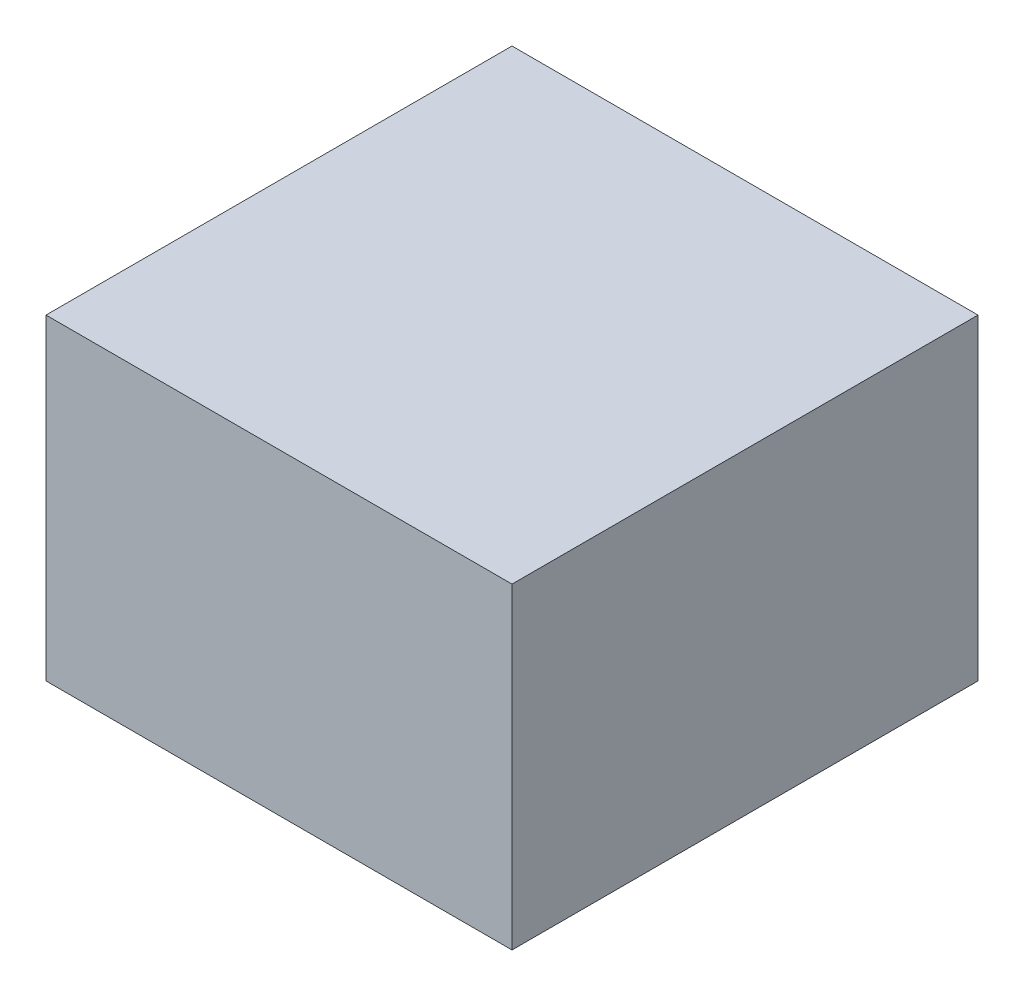
SolidWorks part; units mm, degrees
material "1060 Alloy"
ref_plane "Front Plane" through (0, 0, 0) normal (0, 0, 1) x (1, 0, 0)
ref_plane "Top Plane" through (0, 0, 0) normal (0, 1, 0) x (1, 0, 0)
ref_plane "Right Plane" through (0, 0, 0) normal (1, 0, 0) x (0, 0, -1)
sketch "Sketch1" plane through (0, 0, 0) normal (0, 1, 0) x (1, 0, 0)
  line L0 (0, 0) -> (50, 0)
  line L1 (50, 0) -> (50, 100)
  line L2 (50, 100) -> (-50, 100)
  line L3 (-50, 100) -> (-50, 0)
  line L4 (-50, 0) -> (0, 0)
  line L5 (50, 0) -> (100, 0)
  line L6 (100, 0) -> (150, 0)
  line L7 (150, 0) -> (150, 100)
  line L8 (150, 100) -> (50, 100)
  line L9 (50, 100) -> (50, 0)
  line L10 (150, 0) -> (200, 0)
  line L11 (200, 0) -> (250, 0)
  line L12 (250, 0) -> (250, 100)
  line L13 (250, 100) -> (150, 100)
  line L14 (150, 100) -> (150, 0)
  line L15 (250, 0) -> (300, 0)
  line L16 (300, 0) -> (350, 0)
  line L17 (350, 0) -> (350, 100)
  line L18 (350, 100) -> (250, 100)
  line L19 (250, 100) -> (250, 0)
  line L20 (350, 0) -> (400, 0)
  line L21 (400, 0) -> (450, 0)
  line L22 (450, 0) -> (450, 100)
  line L23 (450, 100) -> (350, 100)
  line L24 (350, 100) -> (350, 0)
  line L25 (50, 100) -> (100, 100)
  line L26 (100, 100) -> (150, 100)
  line L27 (150, 100) -> (150, 200)
  line L28 (150, 200) -> (50, 200)
  line L29 (50, 200) -> (50, 100)
  line L30 (150, 100) -> (200, 100)
  line L31 (200, 100) -> (250, 100)
  line L32 (250, 100) -> (250, 200)
  line L33 (250, 200) -> (150, 200)
  line L34 (150, 200) -> (150, 100)
  line L35 (250, 100) -> (300, 100)
  line L36 (300, 100) -> (350, 100)
  line L37 (350, 100) -> (350, 200)
  line L38 (350, 200) -> (250, 200)
  line L39 (250, 200) -> (250, 100)
  line L40 (350, 100) -> (400, 100)
  line L41 (400, 100) -> (450, 100)
  line L42 (450, 100) -> (450, 200)
  line L43 (450, 200) -> (350, 200)
  line L44 (350, 200) -> (350, 100)
  line L45 (50, 200) -> (100, 200)
  line L46 (100, 200) -> (150, 200)
  line L47 (150, 200) -> (150, 300)
  line L48 (150, 300) -> (50, 300)
  line L49 (50, 300) -> (50, 200)
  line L50 (150, 200) -> (200, 200)
  line L51 (200, 200) -> (250, 200)
  line L52 (250, 200) -> (250, 300)
  line L53 (250, 300) -> (150, 300)
  line L54 (150, 300) -> (150, 200)
  line L55 (250, 200) -> (300, 200)
  line L56 (300, 200) -> (350, 200)
  line L57 (350, 200) -> (350, 300)
  line L58 (350, 300) -> (250, 300)
  line L59 (250, 300) -> (250, 200)
  line L60 (350, 200) -> (400, 200)
  line L61 (400, 200) -> (450, 200)
  line L62 (450, 200) -> (450, 300)
  line L63 (450, 300) -> (350, 300)
  line L64 (350, 300) -> (350, 200)
  line L65 (50, 300) -> (100, 300)
  line L66 (100, 300) -> (150, 300)
  line L67 (150, 300) -> (150, 400)
  line L68 (150, 400) -> (50, 400)
  line L69 (50, 400) -> (50, 300)
  line L70 (150, 300) -> (200, 300)
  line L71 (200, 300) -> (250, 300)
  line L72 (250, 300) -> (250, 400)
  line L73 (250, 400) -> (150, 400)
  line L74 (150, 400) -> (150, 300)
  line L75 (250, 300) -> (300, 300)
  line L76 (300, 300) -> (350, 300)
  line L77 (350, 300) -> (350, 400)
  line L78 (350, 400) -> (250, 400)
  line L79 (250, 400) -> (250, 300)
  line L80 (350, 300) -> (400, 300)
  line L81 (400, 300) -> (450, 300)
  line L82 (450, 300) -> (450, 400)
  line L83 (450, 400) -> (350, 400)
  line L84 (350, 400) -> (350, 300)
  line L85 (50, 400) -> (100, 400)
  line L86 (100, 400) -> (150, 400)
  line L87 (150, 400) -> (150, 500)
  line L88 (150, 500) -> (50, 500)
  line L89 (50, 500) -> (50, 400)
  line L90 (150, 400) -> (200, 400)
  line L91 (200, 400) -> (250, 400)
  line L92 (250, 400) -> (250, 500)
  line L93 (250, 500) -> (150, 500)
  line L94 (150, 500) -> (150, 400)
  line L95 (250, 400) -> (300, 400)
  line L96 (300, 400) -> (350, 400)
  line L97 (350, 400) -> (350, 500)
  line L98 (350, 500) -> (250, 500)
  line L99 (250, 500) -> (250, 400)
  line L100 (350, 400) -> (400, 400)
  line L101 (400, 400) -> (450, 400)
  line L102 (450, 400) -> (450, 500)
  line L103 (450, 500) -> (350, 500)
  line L104 (350, 500) -> (350, 400)
  line L105 (-50, 100) -> (0, 100)
  line L106 (0, 100) -> (50, 100)
  line L107 (50, 100) -> (50, 200)
  line L108 (50, 200) -> (-50, 200)
  line L109 (-50, 200) -> (-50, 100)
  line L110 (-50, 200) -> (0, 200)
  line L111 (0, 200) -> (50, 200)
  line L112 (50, 200) -> (50, 300)
  line L113 (50, 300) -> (-50, 300)
  line L114 (-50, 300) -> (-50, 200)
  line L115 (-50, 300) -> (0, 300)
  line L116 (0, 300) -> (50, 300)
  line L117 (50, 300) -> (50, 400)
  line L118 (50, 400) -> (-50, 400)
  line L119 (-50, 400) -> (-50, 300)
  line L120 (-50, 400) -> (0, 400)
  line L121 (0, 400) -> (50, 400)
  line L122 (50, 400) -> (50, 500)
  line L123 (50, 500) -> (-50, 500)
  line L124 (-50, 500) -> (-50, 400)
  dimension "D1" = 5
  dimension "D2" = 5
extrude "Boss-Extrude1" add sketch "Sketch1" along normal blind 340 contours L123 L124 L118 L89 | L88 L89 L68 L87 | L92 L93 L87 L73 | L102 L103 L97 L83 | L97 L98 L92 L78 | L77 L78 L72 L58 | L68 L69 L48 L67 | L72 L73 L67 L53 | L118 L119 L113 L69 | L113 L114 L108 L49 | L52 L53 L47 L33 | L57 L58 L52 L38 | L62 L63 L57 L43 | L82 L83 L77 L63 | L42 L43 L37 L23 | L37 L38 L32 L18 | L32 L33 L27 L13 | L108 L109 L2 L29 | L3 L4 L0 L1 L2 | L7 L8 L1 L5 L6 | L12 L13 L7 L10 L11 | L17 L18 L12 L15 L16 | L22 L23 L17 L20 L21 | L48 L49 L28 L47
sketch "Sketch2" plane through (0, 0, 0) normal (0, -1, 0) x (-1, 0, 0)
  line L0 (-450, 500) -> (-450, 400)
  line L1 (-450, 0) -> (-450, 500) construction
  line L3 (-350, 400) -> (-350, 500)
  line L4 (-450, 500) -> (50, 500) construction
  line L5 (-350, 500) -> (-450, 500)
  line L6 (-450, 500) -> (-350, 400) construction
  line L7 (-350, 500) -> (-450, 400) construction
  circle A0 centre (-400, 450) radius 31
  circle A1 centre (-300, 450) radius 31
  circle A2 centre (-200, 450) radius 31
  circle A3 centre (-100, 450) radius 31
  circle A4 centre (0, 450) radius 31
  circle A5 centre (-300, 350) radius 31
  circle A6 centre (-200, 350) radius 31
  circle A7 centre (-100, 350) radius 31
  circle A8 centre (0, 350) radius 31
  circle A9 centre (-300, 250) radius 31
  circle A10 centre (-200, 250) radius 31
  circle A11 centre (-100, 250) radius 31
  circle A12 centre (0, 250) radius 31
  circle A13 centre (-300, 150) radius 31
  circle A14 centre (-200, 150) radius 31
  circle A15 centre (-100, 150) radius 31
  circle A16 centre (0, 150) radius 31
  circle A17 centre (-300, 50) radius 31
  circle A18 centre (-200, 50) radius 31
  circle A19 centre (-100, 50) radius 31
  circle A20 centre (0, 50) radius 31
  circle A21 centre (-400, 350) radius 31
  circle A22 centre (-400, 250) radius 31
  circle A23 centre (-400, 150) radius 31
  circle A24 centre (-400, 50) radius 31
  dimension "D1" = 5
  dimension "D2" = 5
extrude "Cut-Extrude1" cut sketch "Sketch2" against normal blind 330 contours A4 | A8 | A12 | A20 | A3 | A7 | A11 | A15 | A19 | A2 | A6 | A10 | A14 | A18 | A1 | A5 | A9 | A13 | A17 | A0 | A21 | A22 | A23 | A24 | A16
sketch "Sketch3" plane through (0, 0, 0) normal (0, -1, 0) x (-1, 0, 0)
  circle A0 centre (-400, 450) radius 40
  circle A1 centre (-300, 450) radius 40
  circle A2 centre (-200, 450) radius 40
  circle A3 centre (-100, 450) radius 40
  circle A4 centre (0, 450) radius 40
  circle A5 centre (-300, 350) radius 40
  circle A6 centre (-200, 350) radius 40
  circle A7 centre (-100, 350) radius 40
  circle A8 centre (0, 350) radius 40
  circle A9 centre (-300, 250) radius 40
  circle A10 centre (-200, 250) radius 40
  circle A11 centre (-100, 250) radius 40
  circle A12 centre (0, 250) radius 40
  circle A13 centre (-300, 150) radius 40
  circle A14 centre (-200, 150) radius 40
  circle A15 centre (-100, 150) radius 40
  circle A16 centre (0, 150) radius 40
  circle A17 centre (-300, 50) radius 40
  circle A18 centre (-200, 50) radius 40
  circle A19 centre (-100, 50) radius 40
  circle A20 centre (0, 50) radius 40
  circle A21 centre (-400, 350) radius 40
  circle A22 centre (-400, 250) radius 40
  circle A23 centre (-400, 150) radius 40
  circle A24 centre (-400, 50) radius 40
  dimension "D1" = 5
  dimension "D2" = 5
extrude "Cut-Extrude3" cut sketch "Sketch3" against normal blind 10
